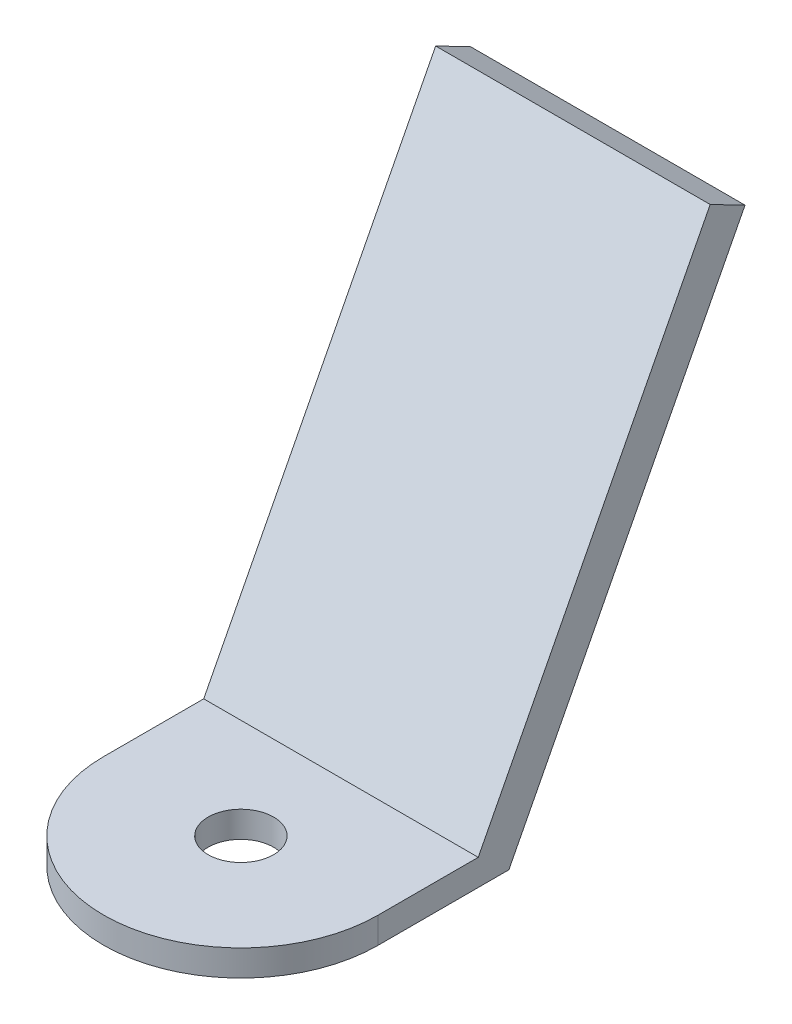
SolidWorks part; units mm, degrees
ref_plane "Front Plane" through (0, 0, 0) normal (0, 0, 1) x (1, 0, 0)
ref_plane "Top Plane" through (0, 0, 0) normal (0, 1, 0) x (1, 0, 0)
ref_plane "Right Plane" through (0, 0, 0) normal (1, 0, 0) x (0, 0, -1)
sketch "Sketch1" plane through (0, 0, 0) normal (0, 1, 0) x (1, 0, 0)
  line L0 (-10.5, 0) -> (-10.5, 10)
  line L1 (-10.5, 10) -> (10.5, 10)
  line L2 (10.5, 10) -> (10.5, 0)
  arc A0 (-10.5, 0) -> (10.5, 0) centre (0, 0) ccw
  circle A1 centre (0, 0) radius 2.5
  dimension "D1" = 10.5
  dimension "D3" = 5
  dimension "D2" = 10
extrude "Boss-Extrude1" add sketch "Sketch1" along normal blind 2
sketch "Sketch3" plane through (10.5, 0, 0) normal (1, 0, 0) x (0, 0, -1)
  line L0 (10, 0) -> (10, 19.2) construction
  line L1 (10, 19.2) -> (19.91, 19.2) construction
  line L2 (10, 0) -> (19.91, 19.2)
  line L4 (25.3993, 36.376) -> (6.624, 0)
  line L5 (0, 0) -> (10, 0) construction
  line L6 (6.624, 0) -> (10, 0)
  line L7 (19.91, 19.2) -> (28.0651, 35)
  line L8 (28.0651, 35) -> (25.3993, 36.376)
  dimension "D1" = 19.2
  dimension "D2" = 9.91
  dimension "D3" = 35
  dimension "D4" = 3
extrude "Boss-Extrude3" add sketch "Sketch3" against normal up to surface (21 mm away) up to face at (-10.5, 1, -5)
